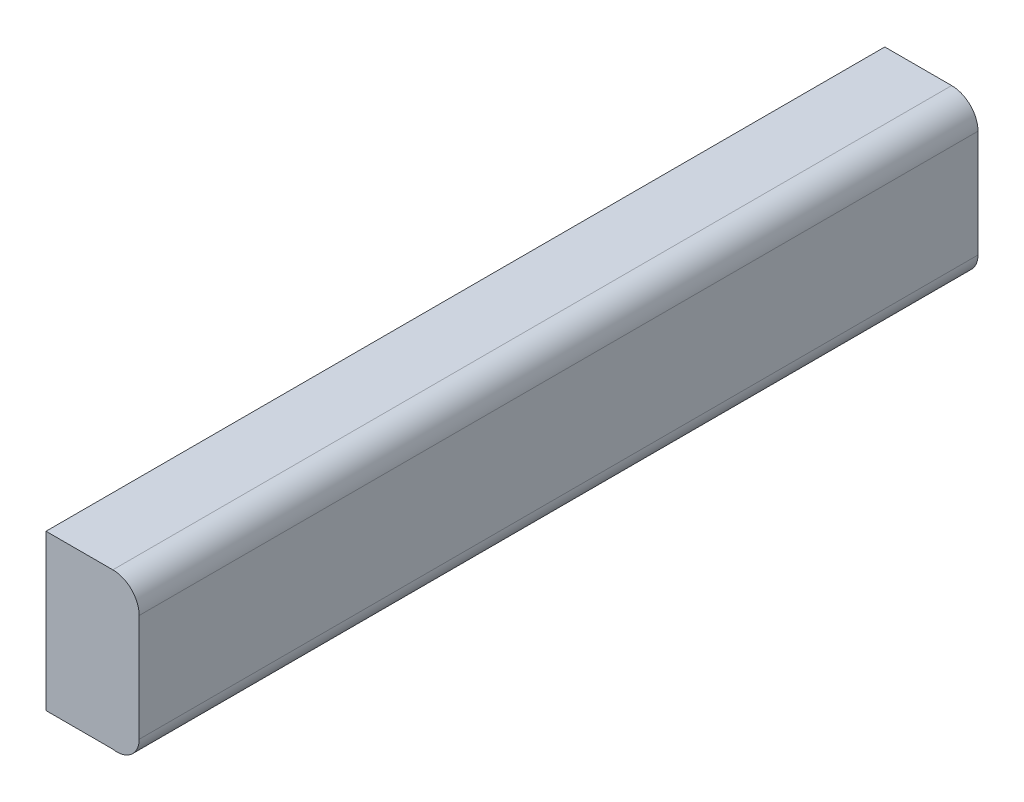
SolidWorks part; units mm, degrees
ref_plane "Front Plane" through (0, 0, 0) normal (0, 0, 1) x (1, 0, 0)
ref_plane "Top Plane" through (0, 0, 0) normal (0, 1, 0) x (1, 0, 0)
ref_plane "Right Plane" through (0, 0, 0) normal (1, 0, 0) x (0, 0, -1)
sketch "Sketch1" plane through (0, 0, 0) normal (0, 0, 1) x (1, 0, 0)
  line L0 (0, 0) -> (54.6564, 0)
  line L1 (76.2, -21.5436) -> (76.2, -109.1917)
  line L2 (54.6564, -127) -> (0, -127)
  line L3 (0, -127) -> (0, 0)
  arc A0 (54.6564, 0) -> (76.2, -21.5436) centre (54.6564, -21.5436) cw
  arc A1 (76.2, -109.1917) -> (54.6564, -127) centre (58.0678, -109.1917) cw
  dimension "D1" = 76.2
  dimension "D2" = 127
extrude "Boss-Extrude1" add sketch "Sketch1" along normal blind 685.8
